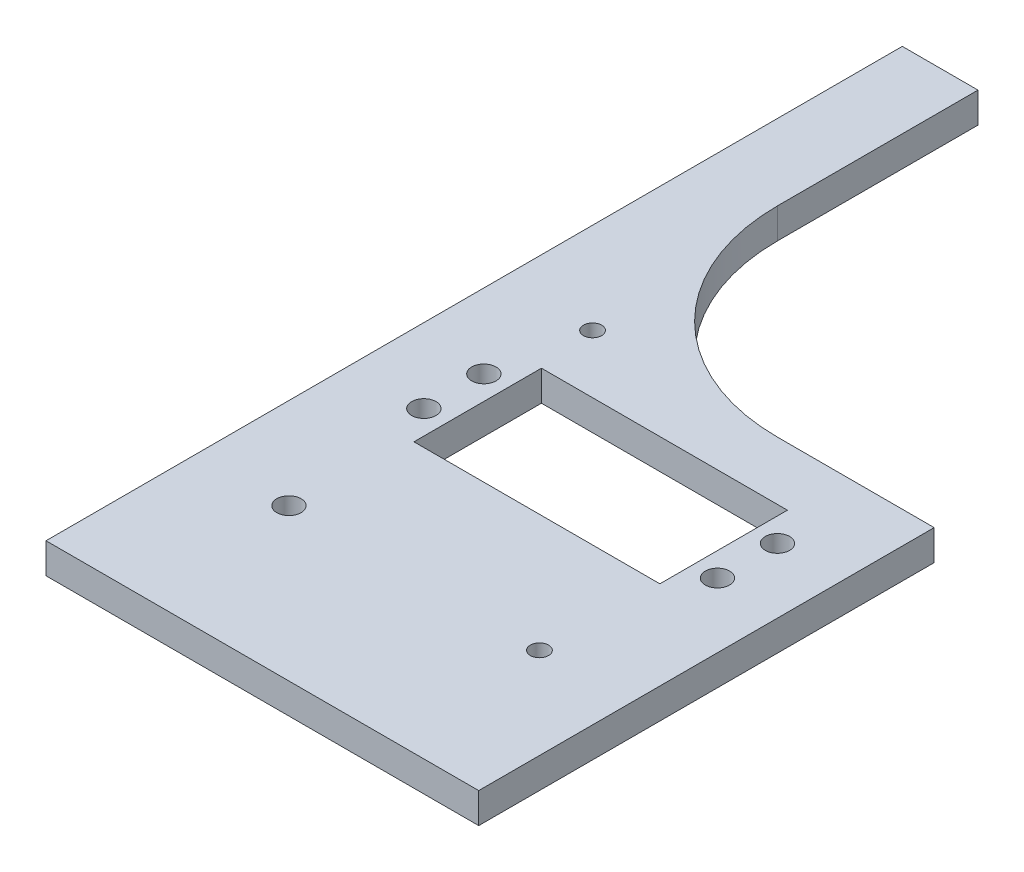
SolidWorks part; units mm, degrees
ref_plane "Front Plane" through (0, 0, 0) normal (0, 0, 1) x (1, 0, 0)
ref_plane "Top Plane" through (0, 0, 0) normal (0, 1, 0) x (1, 0, 0)
ref_plane "Right Plane" through (0, 0, 0) normal (1, 0, 0) x (0, 0, -1)
sketch "Sketch1" plane through (0, 0, 0) normal (0, 1, 0) x (1, 0, 0)
  line L0 (0, 48) -> (0, 33)
  line L1 (-45.4667, 13.2678) -> (7.0696, 13.2678)
  line L2 (-45.4667, 13.2678) -> (-45.4667, -47.4725)
  line L3 (-45.4667, -47.4725) -> (7.0696, -47.4725)
  line L4 (7.0696, 13.2678) -> (7.0696, -47.4725)
  line L5 (-45.4667, -33) -> (25.7862, -33)
  line L6 (-45.4667, -33) -> (-45.4667, -107.9997)
  line L7 (-45.4667, -107.9997) -> (25.7862, -107.9997)
  line L8 (25.7862, -33) -> (25.7862, -107.9997)
  line L9 (0, -33) -> (0, -48)
  line L10 (0, 0) -> (-33, 0) construction
  line L15 (-33, 0) -> (-33, 13.2678)
  line L17 (-33, 13.2678) -> (-45.4667, 13.2678)
  line L18 (-33.2067, -48.16) -> (25.7862, -48.16) construction
  line L19 (11.2162, -42.6) -> (-29.2838, -42.6)
  line L20 (11.2162, -42.6) -> (11.2162, -63.6)
  line L21 (11.2162, -63.6) -> (-29.2838, -63.6)
  line L22 (-29.2838, -42.6) -> (-29.2838, -63.6)
  line L23 (15.1362, -48.16) -> (15.1362, -58.04) construction
  line L24 (15.1362, -58.04) -> (-33.2067, -58.04) construction
  line L25 (10.7862, -83) -> (-33.2067, -83) construction
  line L26 (-33, 13.2678) -> (-33, 33)
  line L27 (-33, 33) -> (-45.4667, 33)
  line L28 (-45.4667, 13.2678) -> (-45.4667, 33)
  circle A0 centre (0, 0) radius 33
  circle A1 centre (0, 0) radius 48
  circle A2 centre (-30.4667, -33) radius 1.5
  circle A3 centre (-33.2067, -48.16) radius 2
  circle A4 centre (-33.2067, -58.04) radius 2
  circle A5 centre (15.1362, -48.16) radius 2
  circle A6 centre (15.1362, -58.04) radius 2
  circle A7 centre (10.7862, -83) radius 1.5
  circle A8 centre (-30.4638, -83) radius 2
  point P20 (-39.23, 16.522)
  dimension "D1" = 66
  dimension "D2" = 96
  dimension "D10" = 3
  dimension "D11" = 15
  dimension "D12" = 4
  dimension "D13" = 12.26
  dimension "D14" = 5.56
  dimension "D15" = 9.88
  dimension "D16" = 4
  dimension "D17" = 4
  dimension "D18" = 10.65
  dimension "D19" = 4
  dimension "D20" = 3
  dimension "D21" = 19.4
  dimension "D22" = 15
  dimension "D23" = 4
  dimension "D24" = 41.25
  dimension "D3" = 71.253
  dimension "D4" = 74.9997
  dimension "D5" = 19.7322
  dimension "D6" = 9.6
  dimension "D7" = 14.57
  dimension "D8" = 40.5
  dimension "D9" = 21
  dimension "D25" = 46.2678
  dimension "D26" = 12.4667
extrude "Boss-Extrude1" add sketch "Sketch1" along normal mid plane 5 contours A1 L27 L28 | L27 A1 L28 L1 L26 | A2 L5 A0 L15 L1 L2 A1 | A3 L3 L22 L19 A1 L5 L2 | A1 L2 L5 | A2 L5 A1 L19 L9 | L19 L4 L5 L9 | L20 A1 L8 L5 L4 L19 | A3 L3 L6 L7 L8 A1 L20 L21 L22 A8 A7 A6 A5 A4
